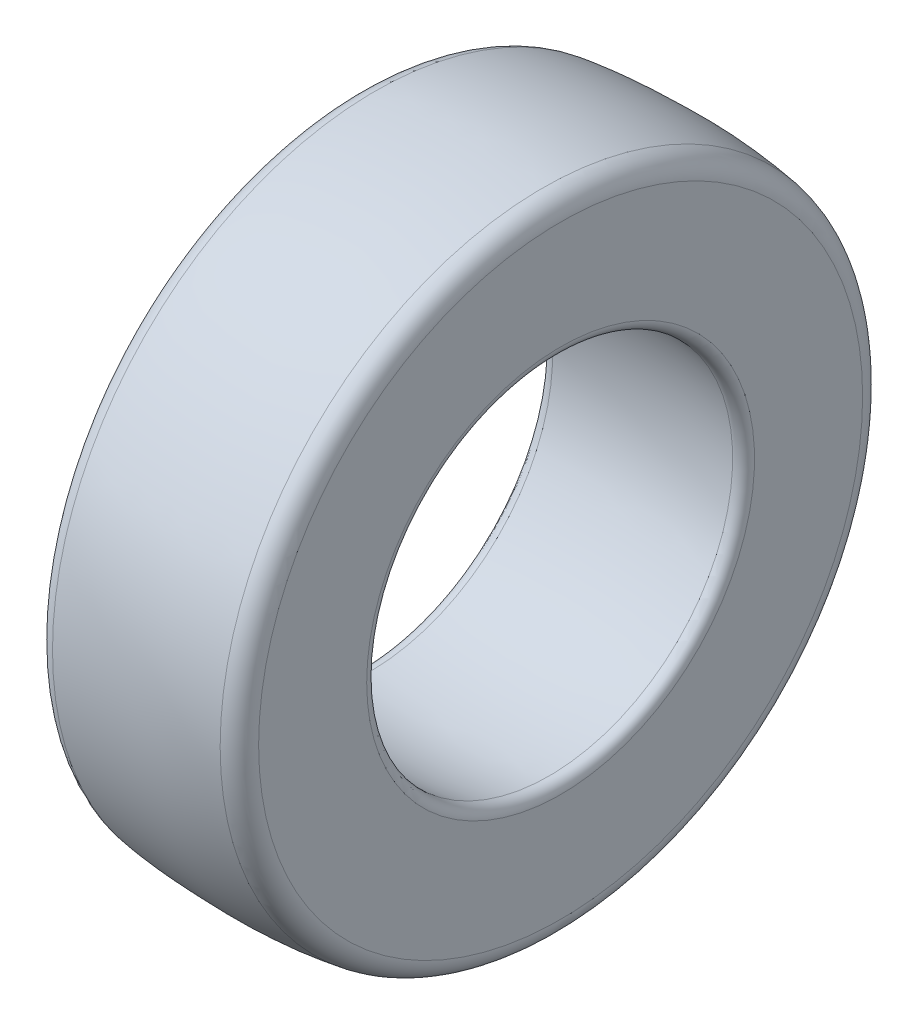
SolidWorks part; units mm, degrees
material "BUTYL"
ref_plane "Plan de face" through (0, 0, 0) normal (0, 0, 1) x (1, 0, 0)
ref_plane "Plan de dessus" through (0, 0, 0) normal (0, 1, 0) x (1, 0, 0)
ref_plane "Plan de droite" through (0, 0, 0) normal (1, 0, 0) x (0, 0, -1)
sketch "Esquisse1" plane through (0, 0, 0) normal (0, 0, 1) x (1, 0, 0)
  line L0 (0, 0.8011) -> (0, -8.8091) construction
  line L1 (9.75, -1.7058) -> (9.75, -12.0805)
  line L3 (-9.75, -1.6936) -> (-9.75, -12.074)
  arc A0 (8.037, 0.2735) -> (9.75, -1.7058) centre (7.75, -1.7058) cw
  arc A1 (-8.0469, 0.2842) -> (-9.75, -1.6936) centre (-7.75, -1.6936) ccw
  arc A2 (9.75, -12.0805) -> (8.6442, -13.0749) centre (8.75, -12.0805) cw
  arc A3 (-9.75, -12.074) -> (-8.6395, -13.0679) centre (-8.75, -12.074) ccw
  spline S0 degree 3 poles (-8.0469, 0.2842) (-5.7094, 0.6351) (1.5391, 0.9396) (5.0004, 0.7137) (8.037, 0.2735) knots 0.089501 0.089501 0.089501 0.089501 0.457116 0.914232 0.914232 0.914232 0.914232
  spline S1 degree 3 poles (-8.6395, -13.0679) (-5.9627, -12.7703) (1.019, -12.4808) (5.4012, -12.7299) (8.6442, -13.0749) knots 0.057341 0.057341 0.057341 0.057341 0.473274 0.946548 0.946548 0.946548 0.946548
  dimension "D1" = 2
  dimension "D3" = 1
  dimension "D2" = 13.4184
sketch "Esquisse2" plane through (0, 0, 0) normal (1, 0, 0) x (0, 0, -1)
  line L0 (0, 200000.8011) -> (0, -200008.8091) construction
  circle A0 centre (0, -30.6973) radius 18.08
  dimension "D1" = 36.16
  dimension "D2" = 18.08
sweep "Balayage1" add profiles "Esquisse1" path "Esquisse2"
sketch "Esquisse4" plane through (0, 0, 0) normal (1, 0, 0) x (0, 0, -1)
  circle A0 centre (0, -30.6973) radius 20 construction
  dimension "D1" = 40
